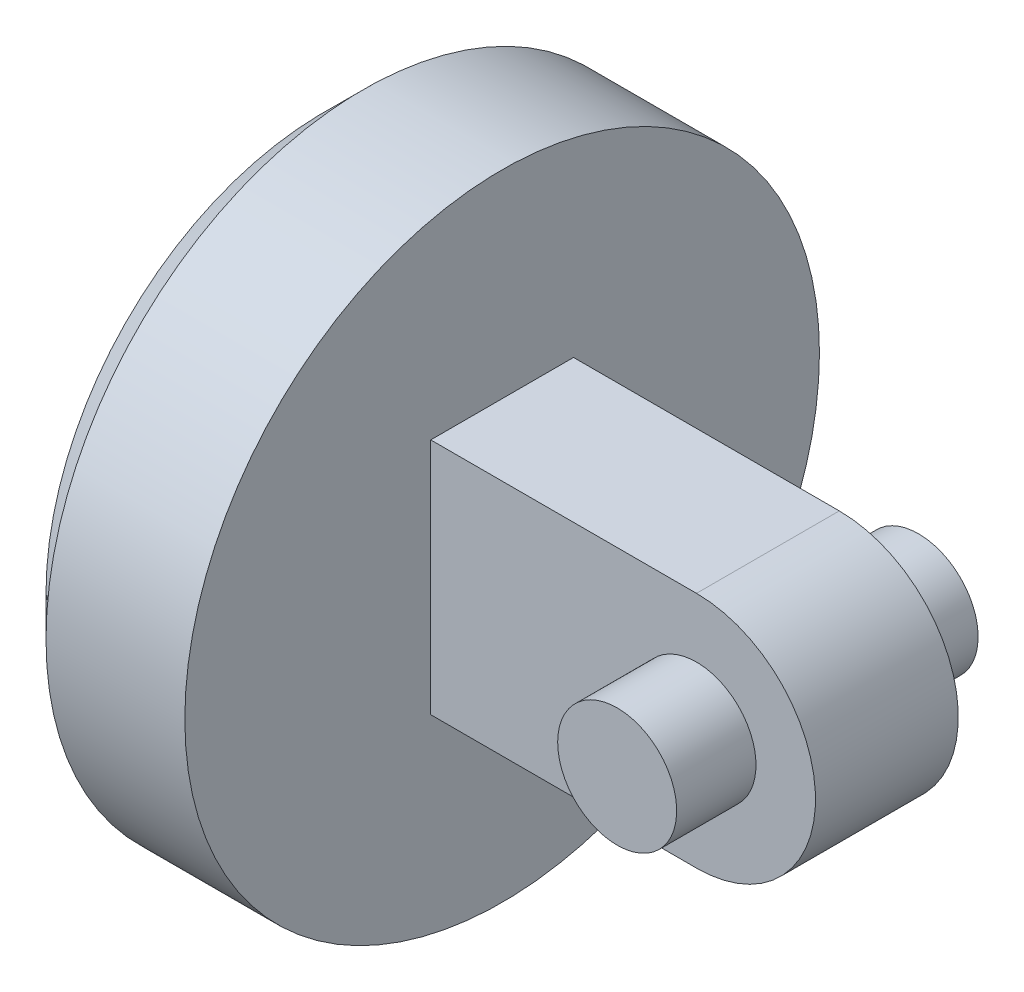
SolidWorks part; units mm, degrees
ref_plane "前视基准面" through (0, 0, 0) normal (0, 0, 1) x (1, 0, 0)
ref_plane "上视基准面" through (0, 0, 0) normal (0, 1, 0) x (1, 0, 0)
ref_plane "右视基准面" through (0, 0, 0) normal (1, 0, 0) x (0, 0, -1)
sketch "草图1" plane through (0, 0, 0) normal (0, 0, 1) x (1, 0, 0)
  line B0 (-4.5, 7) -> (-4.5, 0)
  line B1 (-4.5, 0) -> (0, 0)
  line B2 (-3.5, 8) -> (0, 8)
  line B3 (-4.5, 7) -> (-3.5, 8)
  line B4 (0, 8) -> (0, 0)
sketch_block_instance "A$C528E6A85-1"
sketch_block "A$C528E6A85"
revolve "旋转1" add sketch "草图1" angle 360 about L1
sketch "草图3" plane through (0, 0, 0) normal (0, 0, 1) x (1, 0, 0)
  line L1 (0, -3) -> (6.7, -3)
  line L2 (0, 3) -> (6.7, 3)
  line L3 (0, 3) -> (0, -3)
  arc A0 (6.7, -3) -> (6.7, 3) centre (6.7, 0) ccw
extrude "凸台-拉伸1" add sketch "草图3" along normal mid plane 3.6
sketch "草图4" plane through (0, 0, 0) normal (0, 1, 0) x (1, 0, 0)
  line L0 (6.7, -1.8) -> (6.7, -3.8)
  line L1 (6.7, -3.8) -> (8.2, -3.8)
  line L2 (8.2, -3.8) -> (8.2, -1.8)
  line L3 (6.7, -1.8) -> (9.7, -1.8) construction
  line L4 (8.2, -1.8) -> (6.7, -1.8)
revolve "旋转2" add sketch "草图4" angle 360 about L0
mirror "镜向1" about plane through (0, 0, 0) normal (0, 0, 1) of "旋转2"
